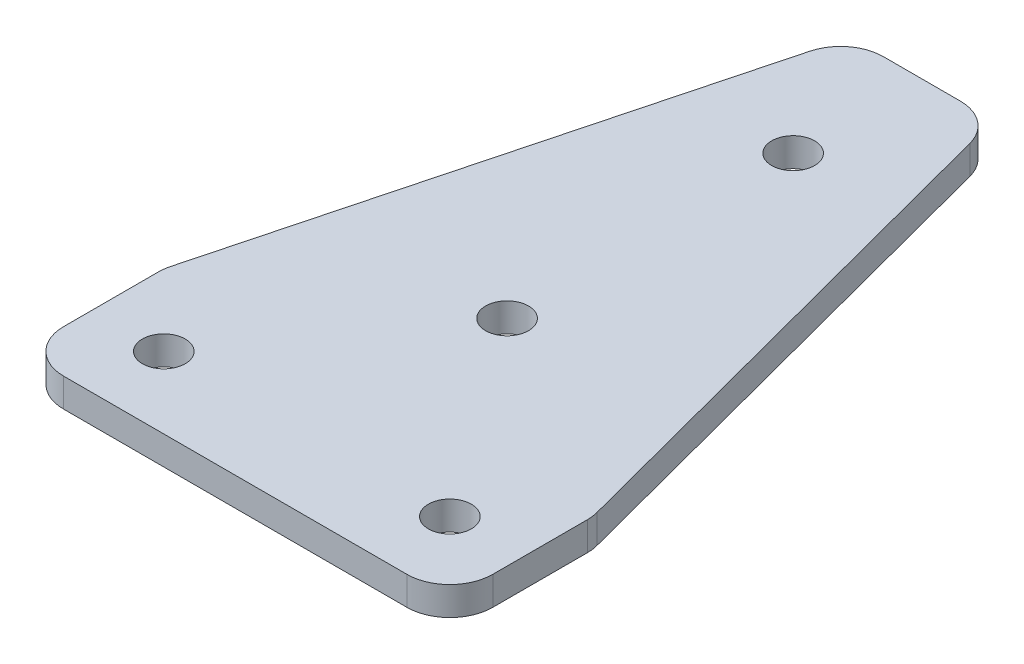
SolidWorks part; units mm, degrees
ref_plane "前视基准面" through (0, 0, 0) normal (0, 0, 1) x (1, 0, 0)
ref_plane "上视基准面" through (0, 0, 0) normal (0, 1, 0) x (1, 0, 0)
ref_plane "右视基准面" through (0, 0, 0) normal (1, 0, 0) x (0, 0, -1)
other "Configuration Table"
sketch "草图1" plane through (0, 0, 0) normal (0, 1, 0) x (1, 0, 0)
  line L0 (0, 0) -> (0, 48) construction
  line L1 (-5, 48) -> (5, 48)
  line L2 (-5, 48) -> (-5, 10) construction
  line L3 (-5, 10) -> (-15, 10) construction
  line L4 (-15, 10) -> (-15, 0)
  line L5 (-15, 0) -> (15, 0)
  line L6 (15, 10) -> (15, 0)
  line L7 (5, 10) -> (15, 10) construction
  line L8 (5, 48) -> (5, 10) construction
  line L9 (-10, 5) -> (10, 5) construction
  line L10 (-15, 10) -> (-5, 48)
  line L11 (5, 48) -> (15, 10)
  circle A0 centre (0, 39) radius 1.5
  circle A1 centre (0, 19) radius 1.5
  circle A5 centre (10, 5) radius 1.5
  circle A6 centre (-10, 5) radius 1.5
  point P15 (0, 5)
  point P16 (0, 38.145)
  dimension "D9" = 3
  dimension "D1" = 38
  dimension "D2" = 30
  dimension "D3" = 10
  dimension "D4" = 10
  dimension "D5" = 20
  dimension "D6" = 5
  dimension "D7" = 9
  dimension "D8" = 20
extrude "凸台-拉伸1" add sketch "草图1" along normal blind 2
fillet "圆角1" radius 3 6 edges at (-15, 1, 0) (15, 1, 0) (-5, 1, -48) (5, 1, -48) (15, 1, -10) (-15, 1, -10)
